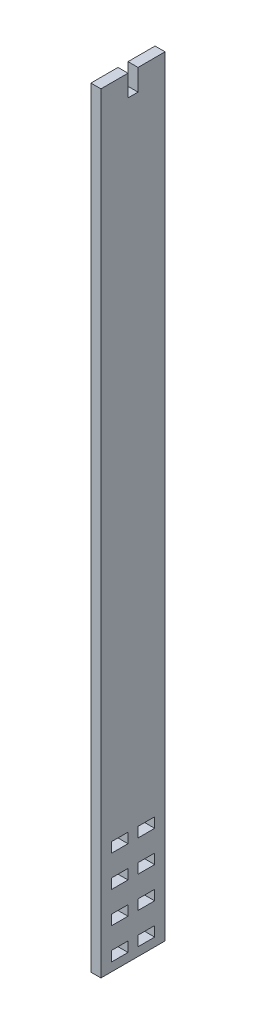
SolidWorks part; units mm, degrees
ref_plane "Front Plane" through (0, 0, 0) normal (1, 0, 0) x (0, 1, 0)
ref_plane "Top Plane" through (0, 0, 0) normal (0, 0, 1) x (0, 1, 0)
ref_plane "Right Plane" through (0, 0, 0) normal (0, 1, 0) x (-1, 0, 0)
sketch "Sketch1" plane through (0, 0, 0) normal (1, 0, 0) x (0, 1, 0)
  line L1 (-114.3, -9.525) -> (114.3, -9.525)
  line L2 (-114.3, -9.525) -> (-114.3, 9.525)
  line L3 (-114.3, 9.525) -> (114.3, 9.525)
  line L4 (114.3, -9.525) -> (114.3, 9.525)
  line L5 (-114.3, -9.525) -> (114.3, 9.525) construction
  line L6 (-114.3, 9.525) -> (114.3, -9.525) construction
  point P0 (0, 0)
  dimension "D1" = 228.6
  dimension "D2" = 19.05
extrude "Boss-Extrude1" add sketch "Sketch1" along normal blind 2.9718
sketch "Sketch3" plane through (2.9718, 0, 0) normal (1, 0, 0) x (0, 1, 0)
  line L0 (114.3, 1.4859) -> (114.3, -1.4859)
  line L1 (114.3, 1.4859) -> (107.95, 1.4859)
  line L2 (114.3, -1.4859) -> (107.95, -1.4859)
  line L3 (107.95, 1.4859) -> (107.95, -1.4859)
  line L4 (114.3, -9.525) -> (114.3, 9.525) construction
  line L5 (0, 0) -> (163.9175, 0) construction
  dimension "D1" = 2.9718
  dimension "D2" = 6.35
extrude "Cut-Extrude1" cut sketch "Sketch3" against normal through all
sketch "Sketch4" plane through (2.9718, 0, 0) normal (1, 0, 0) x (0, 1, 0)
  line L0 (-114.3, 0) -> (221.197, 0) construction
  line L1 (-114.3, 9.525) -> (-114.3, -9.525) construction
  line L26 (-102.4382, 6.35) -> (-99.4664, 6.35)
  line L27 (-111.76, 6.35) -> (-108.7882, 6.35)
  line L28 (-111.76, 6.35) -> (-111.76, 1.4859)
  line L29 (-111.76, 1.4859) -> (-108.7882, 1.4859)
  line L30 (-108.7882, 6.35) -> (-108.7882, 1.4859)
  line L31 (-111.76, -1.4859) -> (-108.7882, -1.4859)
  line L32 (-111.76, -1.4859) -> (-111.76, -6.4305)
  line L33 (-111.76, -6.4305) -> (-108.7882, -6.4305)
  line L34 (-108.7882, -1.4859) -> (-108.7882, -6.4305)
  line L35 (-102.4382, 6.35) -> (-102.4382, 1.4859)
  line L36 (-102.4382, 1.4859) -> (-99.4664, 1.4859)
  line L37 (-99.4664, 6.35) -> (-99.4664, 1.4859)
  line L38 (-102.4382, -1.4859) -> (-99.4664, -1.4859)
  line L39 (-102.4382, -1.4859) -> (-102.4382, -6.4305)
  line L40 (-102.4382, -6.4305) -> (-99.4664, -6.4305)
  line L41 (-99.4664, -1.4859) -> (-99.4664, -6.4305)
  line L42 (-93.1164, 6.35) -> (-90.1446, 6.35)
  line L43 (-93.1164, 6.35) -> (-93.1164, 1.4859)
  line L44 (-93.1164, 1.4859) -> (-90.1446, 1.4859)
  line L45 (-90.1446, 6.35) -> (-90.1446, 1.4859)
  line L46 (-93.1164, -1.4859) -> (-90.1446, -1.4859)
  line L47 (-93.1164, -1.4859) -> (-93.1164, -6.4305)
  line L48 (-93.1164, -6.4305) -> (-90.1446, -6.4305)
  line L49 (-90.1446, -1.4859) -> (-90.1446, -6.4305)
  line L74 (-83.7946, 6.35) -> (-80.8228, 6.35)
  line L75 (-83.7946, 6.35) -> (-83.7946, 1.4859)
  line L76 (-83.7946, 1.4859) -> (-80.8228, 1.4859)
  line L77 (-80.8228, 6.35) -> (-80.8228, 1.4859)
  line L78 (-83.7946, -1.4859) -> (-80.8228, -1.4859)
  line L79 (-83.7946, -1.4859) -> (-83.7946, -6.4305)
  line L80 (-83.7946, -6.4305) -> (-80.8228, -6.4305)
  line L81 (-80.8228, -1.4859) -> (-80.8228, -6.4305)
  point P61 (0, 0)
  point P62 (0, 0)
  point P63 (0, 0)
  dimension "D2" = 2.9718
  dimension "D3" = 2.9718
  dimension "D4" = 2.9718
  dimension "D5" = 6.35
  dimension "D6" = 2.9718
  dimension "D7" = 2.9718
  dimension "D8" = 2.9718
  dimension "D9" = 2.9718
  dimension "D10" = 2.9718
  dimension "D11" = 2.9718
  dimension "D12" = 6.35
  dimension "D13" = 6.35
  dimension "D14" = 6.35
  dimension "D15" = 6.35
  dimension "D16" = 6.35
  dimension "D17" = 6.4305
  dimension "D18" = 6.35
  dimension "D19" = 2.54
  dimension "D20" = 2.54
extrude "Cut-Extrude2" cut sketch "Sketch4" against normal through all
